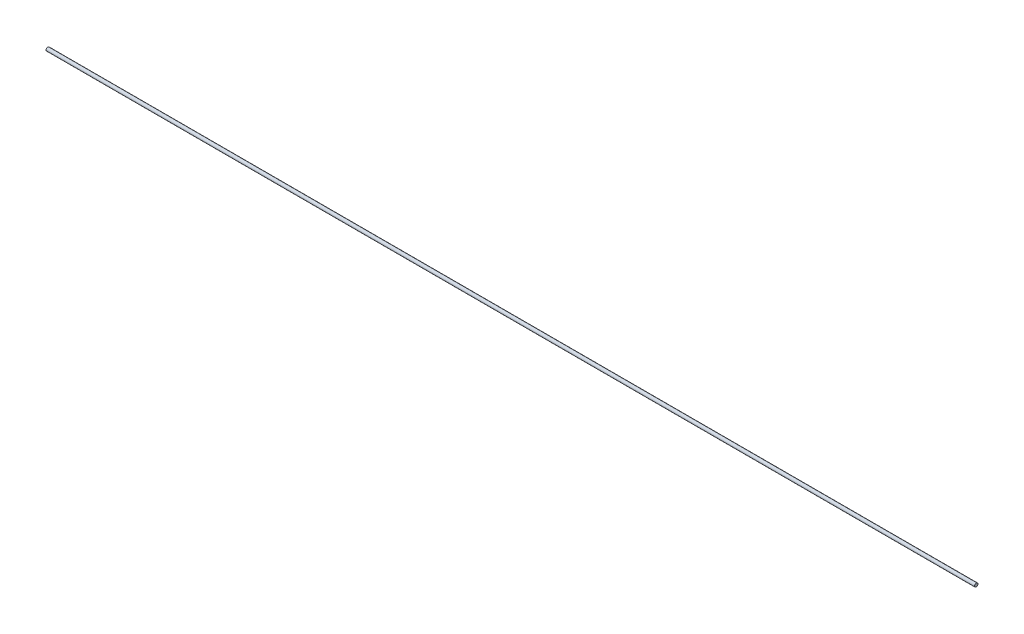
SolidWorks part; units mm, degrees
ref_plane "Front" through (0, 0, 0) normal (0, 0, 1) x (1, 0, 0)
ref_plane "Top" through (0, 0, 0) normal (0, 1, 0) x (1, 0, 0)
ref_plane "Right" through (0, 0, 0) normal (1, 0, 0) x (0, 0, -1)
sketch "Sketch1" plane through (0, 0, 0) normal (0, 0, 1) x (1, 0, 0)
  line L0 (0, 0) -> (34.3951, 0) construction
  line L1 (0, 0) -> (0, 3.175)
  line L2 (0, 3.175) -> (1711.2176, 3.175)
  line L3 (1711.2176, 3.175) -> (1711.2176, 0)
  line L4 (1711.2176, 0) -> (0, 0)
  line L5 (1711.2176, 3.25) -> (1711.2176, -3.25) construction
  dimension "D1" = 6.35
revolve "Revolve1" add sketch "Sketch1" angle 360 about L0
